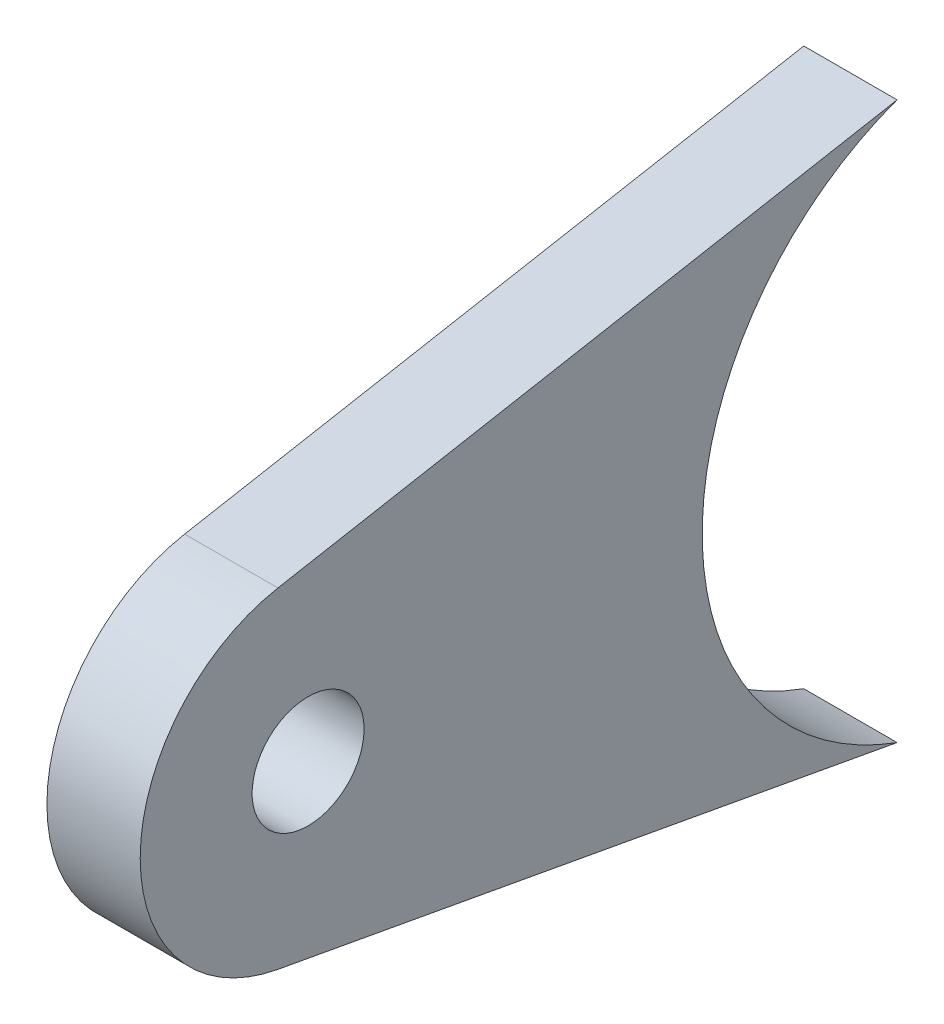
SolidWorks part; units mm, degrees
ref_plane "Front Plane" through (0, 0, 0) normal (1, 0, 0) x (0, 1, 0)
ref_plane "Top Plane" through (0, 0, 0) normal (0, 0, 1) x (0, 1, 0)
ref_plane "Right Plane" through (0, 0, 0) normal (0, 1, 0) x (-1, 0, 0)
sketch "Sketch1" plane through (0, 0, 0) normal (1, 0, 0) x (0, 1, 0)
  line L0 (0, 0) -> (0, 37) construction
  line L1 (-15.875, 0) -> (15.875, 0) construction
  line L2 (0, 0) -> (-14.9176, 5.4296) construction
  line L3 (0, 0) -> (14.9176, 5.4296) construction
  line L4 (-14.9176, 5.4296) -> (-8.8534, 38.6177)
  line L5 (14.9176, 5.4296) -> (8.8534, 38.6177)
  arc A0 (14.9176, 5.4296) -> (-14.9176, 5.4296) centre (0, 0) ccw
  circle A1 centre (0, 37) radius 3
  arc A2 (8.8534, 38.6177) -> (-8.8534, 38.6177) centre (0, 37) ccw
  arc A3 (-8.8534, 38.6177) -> (0, 28) centre (0, 37) ccw construction
  arc A4 (0, 28) -> (8.8534, 38.6177) centre (0, 37) ccw construction
  arc A5 (-15.875, 0) -> (15.875, 0) centre (0, 0) ccw construction
  arc A6 (-14.9176, 5.4296) -> (-15.875, 0) centre (0, 0) ccw construction
  arc A7 (15.875, 0) -> (14.9176, 5.4296) centre (0, 0) ccw construction
  point P9 (0, 0)
  dimension "D2" = 6
  dimension "D1" = 31.75
  dimension "D3" = 18
  dimension "D4" = 37
  dimension "D5" = 20
extrude "Boss-Extrude1" add sketch "Sketch1" along normal mid plane 5
